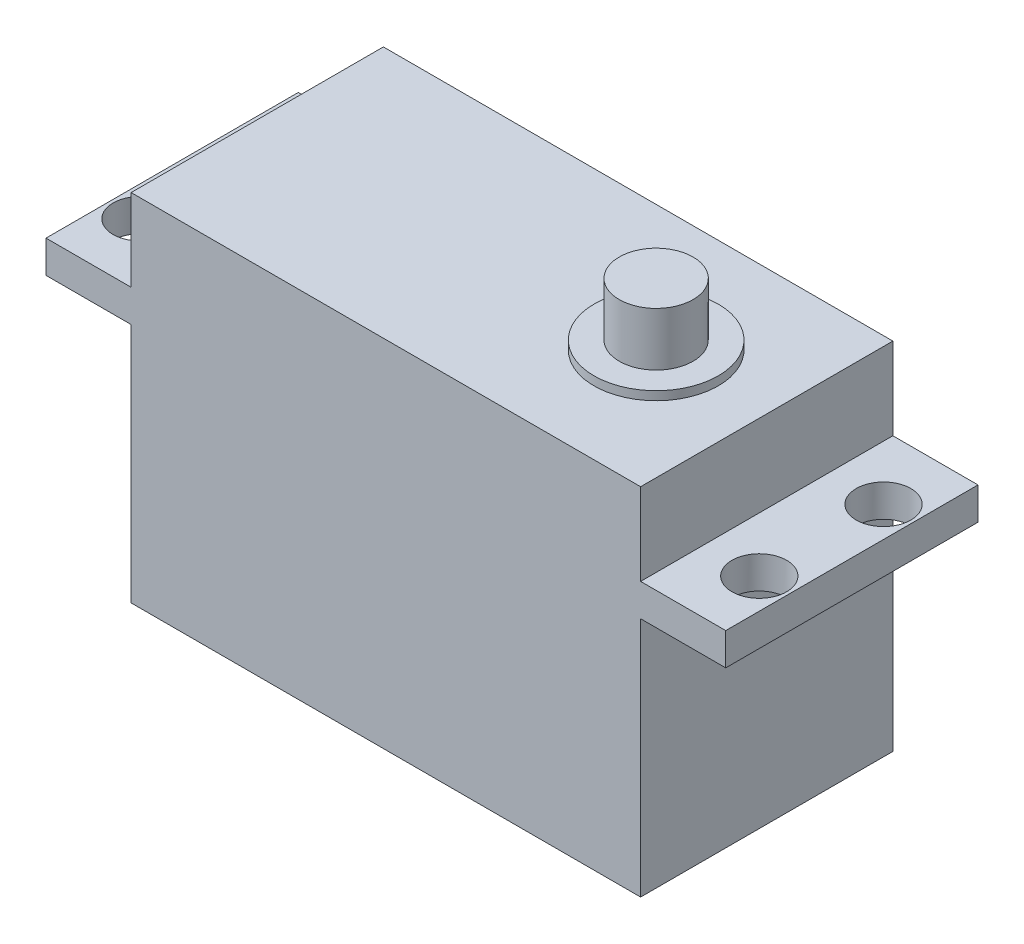
SolidWorks part; units mm, degrees
material "PF"
ref_plane "Front" through (0, 0, 0) normal (0, 0, 1) x (1, 0, 0)
ref_plane "Top" through (0, 0, 0) normal (0, 1, 0) x (1, 0, 0)
ref_plane "Right" through (0, 0, 0) normal (1, 0, 0) x (0, 0, -1)
sketch "Sketch1" plane through (0, 0, 0) normal (0, 0, 1) x (1, 0, 0)
  line L1 (0, 0) -> (41, 0)
  line L2 (0, 0) -> (0, -19.4)
  line L3 (0, -19.4) -> (41, -19.4)
  line L4 (41, 0) -> (41, -19.4)
  dimension "D1" = 41
  dimension "D2" = 19.4
extrude "Boss-Extrude1" add sketch "Sketch1" along normal blind 20.3
sketch "Sketch2" plane through (0, 0, 0) normal (0, 1, 0) x (1, 0, 0)
  line L0 (41, -20.3) -> (0, -20.3) construction
  line L1 (-6.85, -20.3) -> (47.85, -20.3)
  line L2 (-6.85, -20.3) -> (-6.85, 0)
  line L3 (-6.85, 0) -> (47.85, 0)
  line L4 (47.85, -20.3) -> (47.85, 0)
  line L5 (41, 0) -> (0, 0) construction
  line L6 (41, -20.3) -> (41, 0) construction
  dimension "D1" = 54.7
  dimension "D2" = 6.85
extrude "Boss-Extrude2" add sketch "Sketch2" along normal blind 2.6
sketch "Sketch3" plane through (0, 2.6, 0) normal (0, 1, 0) x (1, 0, 0)
  line L0 (-6.85, -20.3) -> (47.85, -20.3) construction
  line L1 (0, -20.3) -> (41, -20.3)
  line L2 (0, -20.3) -> (0, 0)
  line L3 (0, 0) -> (41, 0)
  line L4 (41, -20.3) -> (41, 0)
  line L5 (47.85, 0) -> (-6.85, 0) construction
  line L6 (47.85, -20.3) -> (47.85, 0) construction
  dimension "D1" = 41
  dimension "D2" = 6.85
extrude "Boss-Extrude3" add sketch "Sketch3" along normal blind 6.6
sketch "Sketch4" plane through (0, 2.6, 0) normal (0, 1, 0) x (1, 0, 0)
  line L0 (-6.85, 0) -> (-6.85, -20.3) construction
  line L1 (47.85, -20.3) -> (47.85, 0) construction
  line L2 (47.85, 0) -> (41, 0) construction
  line L4 (0, 0) -> (-6.85, 0) construction
  circle A0 centre (-4.4, -15.15) radius 2.2
  circle A1 centre (-4.4, -5.15) radius 2.2
  circle A2 centre (45.4, -15.15) radius 2.2
  circle A3 centre (45.4, -5.15) radius 2.2
  point P14 (0, 0)
  dimension "D1" = 4.4
  dimension "D2" = 4.4
  dimension "D3" = 4.4
  dimension "D4" = 4.4
  dimension "D5" = 10
  dimension "D6" = 10
  dimension "D7" = 2.45
  dimension "D8" = 2.45
  dimension "D9" = 5.15
  dimension "D10" = 5.15
extrude "Cut-Extrude1" cut sketch "Sketch4" against normal through all
sketch "Sketch5" plane through (0, 9.2, 0) normal (0, 1, 0) x (1, 0, 0)
  line L0 (41, -20.3) -> (41, 0) construction
  line L1 (0, -20.3) -> (41, -20.3) construction
  circle A0 centre (32.1, -10.15) radius 5
  dimension "D3" = 10
  dimension "D1" = 8.9
  dimension "D2" = 10.15
extrude "Boss-Extrude4" add sketch "Sketch5" along normal blind 0.7
sketch "Sketch6" plane through (0, 9.9, 0) normal (0, 1, 0) x (1, 0, 0)
  circle A0 centre (32.1, -10.15) radius 2.97
  dimension "D1" = 5.94
extrude "Boss-Extrude5" add sketch "Sketch6" along normal blind 4.3
